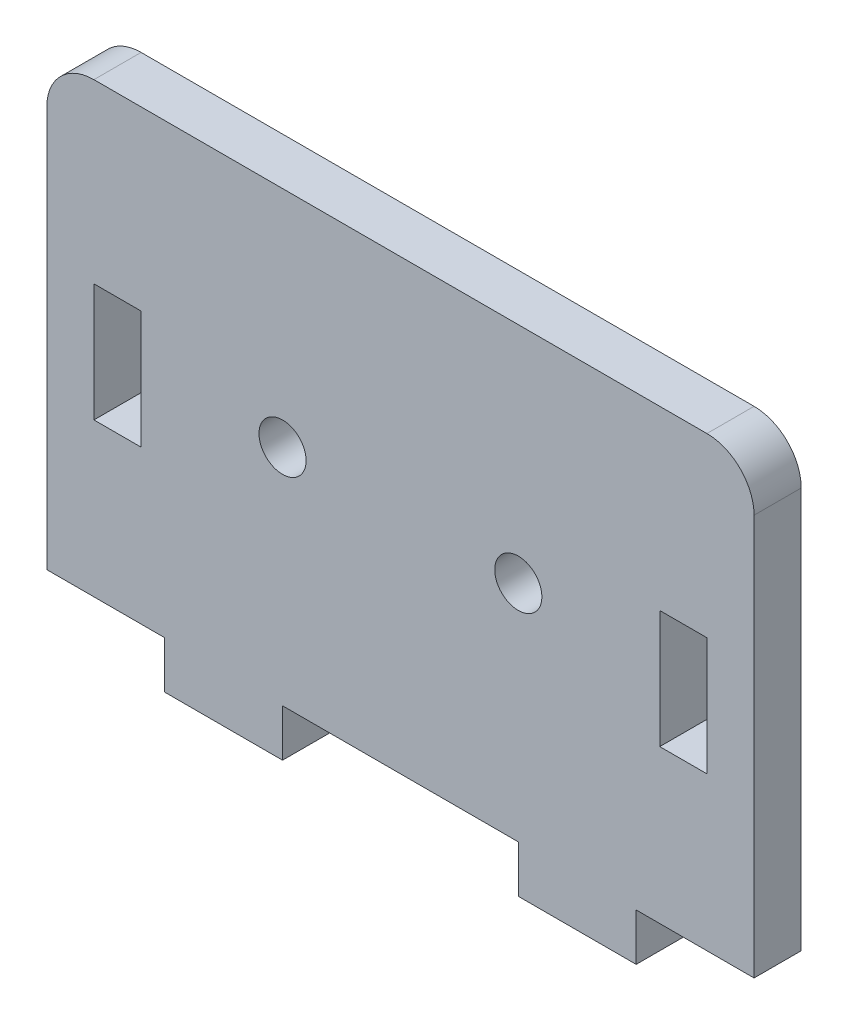
SolidWorks part; units mm, degrees
ref_plane "Front Plane" through (0, 0, 0) normal (0, 0, 1) x (1, 0, 0)
ref_plane "Top Plane" through (0, 0, 0) normal (0, 1, 0) x (1, 0, 0)
ref_plane "Right Plane" through (0, 0, 0) normal (1, 0, 0) x (0, 0, -1)
sketch "Sketch1" plane through (0, 0, 0) normal (0, 0, 1) x (1, 0, 0)
  line L0 (-30, -19) -> (-20, -19)
  line L1 (-26, 19) -> (26, 19)
  line L2 (-30, 15) -> (-30, -19)
  line L3 (-20, -19) -> (-20, -23)
  line L4 (30, 15) -> (30, -19)
  line L5 (-20, -23) -> (-10, -23)
  line L6 (-10, -23) -> (-10, -19)
  line L7 (30, -19) -> (20, -19)
  line L8 (20, -19) -> (20, -23)
  line L9 (20, -23) -> (10, -23)
  line L10 (10, -23) -> (10, -19)
  line L11 (10, -19) -> (-10, -19)
  line L13 (-26, 4) -> (-22, 4)
  line L14 (-26, 4) -> (-26, -6)
  line L15 (-26, -6) -> (-22, -6)
  line L16 (-22, 4) -> (-22, -6)
  line L17 (22, 4) -> (26, 4)
  line L18 (22, 4) -> (22, -6)
  line L19 (22, -6) -> (26, -6)
  line L20 (26, 4) -> (26, -6)
  circle A0 centre (-10, 0) radius 2
  circle A1 centre (10, 0) radius 2
  arc A2 (30, 15) -> (26, 19) centre (26, 15) ccw
  arc A3 (-26, 19) -> (-30, 15) centre (-26, 15) ccw
  point P29 (-30, 19)
  dimension "D7" = 4
  dimension "D15" = 4
  dimension "D1" = 30
  dimension "D2" = 30
  dimension "D3" = 19
  dimension "D4" = 10
  dimension "D5" = 10
  dimension "D6" = 10
  dimension "D8" = 4
  dimension "D9" = 19
  dimension "D10" = 13
  dimension "D11" = 4
  dimension "D12" = 4
  dimension "D13" = 10
  dimension "D14" = 4
extrude "Boss-Extrude1" add sketch "Sketch1" along normal blind 4
